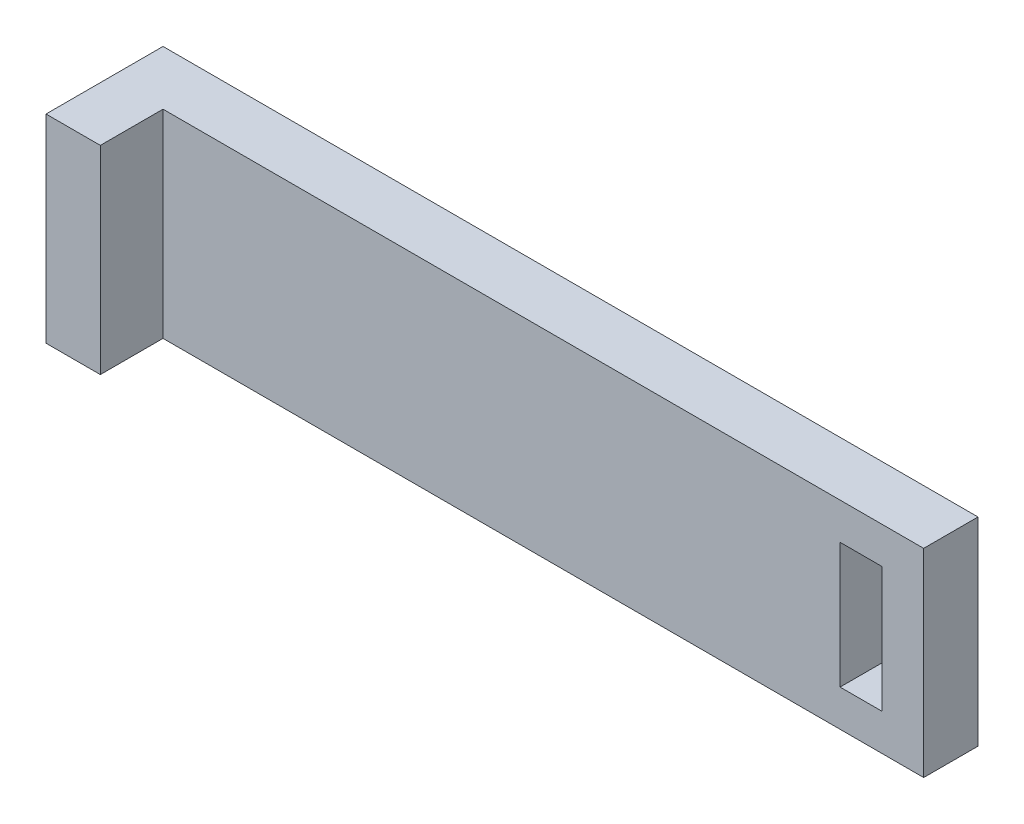
SolidWorks part; units mm, degrees
ref_plane "Front Plane" through (0, 0, 0) normal (0, 0, 1) x (1, 0, 0)
ref_plane "Top Plane" through (0, 0, 0) normal (0, 1, 0) x (1, 0, 0)
ref_plane "Right Plane" through (0, 0, 0) normal (1, 0, 0) x (0, 0, -1)
sketch "Sketch1" plane through (0, 0, 0) normal (0, 0, 1) x (1, 0, 0)
  line L1 (-32.6418, 18.0585) -> (6.3582, 18.0585)
  line L2 (-32.6418, 18.0585) -> (-32.6418, 8.5585)
  line L3 (-32.6418, 8.5585) -> (6.3582, 8.5585)
  line L4 (6.3582, 18.0585) -> (6.3582, 8.5585)
  dimension "D1" = 39
  dimension "D2" = 9.5
extrude "Boss-Extrude1" add sketch "Sketch1" along normal blind 2.6
sketch "Sketch3" plane through (0, 0, 2.6) normal (0, 0, 1) x (1, 0, 0)
  line L0 (-32.6418, 8.5585) -> (6.3582, 8.5585) construction
  line L1 (-32.6418, 18.0585) -> (-30.0418, 18.0585)
  line L2 (-32.6418, 18.0585) -> (-32.6418, 8.5585)
  line L3 (-32.6418, 8.5585) -> (-30.0418, 8.5585)
  line L4 (-30.0418, 18.0585) -> (-30.0418, 8.5585)
  dimension "D1" = 2.6
extrude "Boss-Extrude2" add sketch "Sketch3" along normal blind 3
sketch "Sketch4" plane through (0, 0, 0) normal (0, 0, -1) x (-1, 0, 0)
  line L0 (-6.3582, 18.0585) -> (32.6418, 18.0585) construction
  line L2 (-2.3582, 10.3085) -> (-4.3582, 10.3085)
  line L3 (-2.3582, 10.3085) -> (-2.3582, 16.3085)
  line L4 (-2.3582, 16.3085) -> (-4.3582, 16.3085)
  line L5 (-4.3582, 10.3085) -> (-4.3582, 16.3085)
  line L6 (-6.3582, 8.5585) -> (-6.3582, 18.0585) construction
  dimension "D1" = 6
  dimension "D2" = 1.75
  dimension "D3" = 2
  dimension "D4" = 2
extrude "Cut-Extrude1" cut sketch "Sketch4" against normal blind 4
